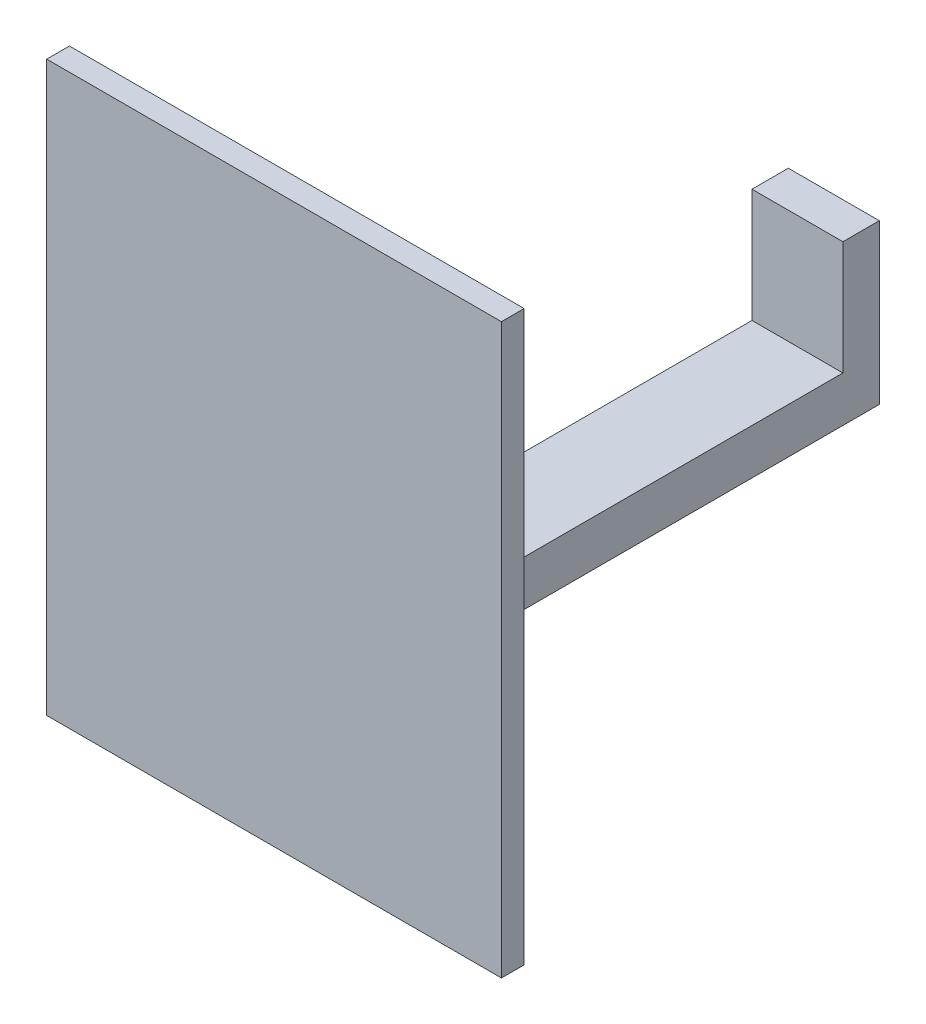
SolidWorks part; units mm, degrees
ref_plane "前视基准面" through (0, 0, 0) normal (0, 0, 1) x (1, 0, 0)
ref_plane "上视基准面" through (0, 0, 0) normal (0, 1, 0) x (1, 0, 0)
ref_plane "右视基准面" through (0, 0, 0) normal (1, 0, 0) x (0, 0, -1)
other "Configuration Table"
sketch "草图1" plane through (0, 0, 0) normal (0, 1, 0) x (1, 0, 0)
  line L1 (-20, 8) -> (20, 8)
  line L2 (-20, 8) -> (-20, -8)
  line L3 (-20, -8) -> (20, -8)
  line L4 (20, 8) -> (20, -8)
  line L5 (-20, 8) -> (20, -8) construction
  line L6 (-20, -8) -> (20, 8) construction
  point P0 (0, 0)
  dimension "D1" = 40
  dimension "D2" = 16
extrude "凸台-拉伸1" add sketch "草图1" along normal blind 70
sketch "草图2" plane through (0, 0, 8) normal (0, 0, 1) x (1, 0, 0)
  line L0 (-20, 70) -> (-20, 0) construction
  line L1 (-20, 20) -> (20, 20)
  line L2 (-20, 20) -> (-20, 0)
  line L3 (-20, 0) -> (20, 0)
  line L4 (20, 20) -> (20, 0)
  dimension "D1" = 40
  dimension "D2" = 20
extrude "凸台-拉伸2" add sketch "草图2" along normal blind 220 contours L2 L1 L4 L3
sketch "草图4" plane through (0, 0, 228) normal (0, 0, 1) x (1, 0, 0)
  line L1 (-100.193, 194.4453) -> (99.807, 194.4453)
  line L2 (-100.193, 194.4453) -> (-100.193, -55.5547)
  line L3 (-100.193, -55.5547) -> (99.807, -55.5547)
  line L4 (99.807, 194.4453) -> (99.807, -55.5547)
  line L5 (-100.193, 194.4453) -> (99.807, -55.5547) construction
  line L6 (-100.193, -55.5547) -> (99.807, 194.4453) construction
  point P0 (-0.193, 69.4453)
  dimension "D1" = 250
  dimension "D2" = 200
extrude "凸台-拉伸4" add sketch "草图4" along normal blind 10 contours L2 L1 L4 L3
